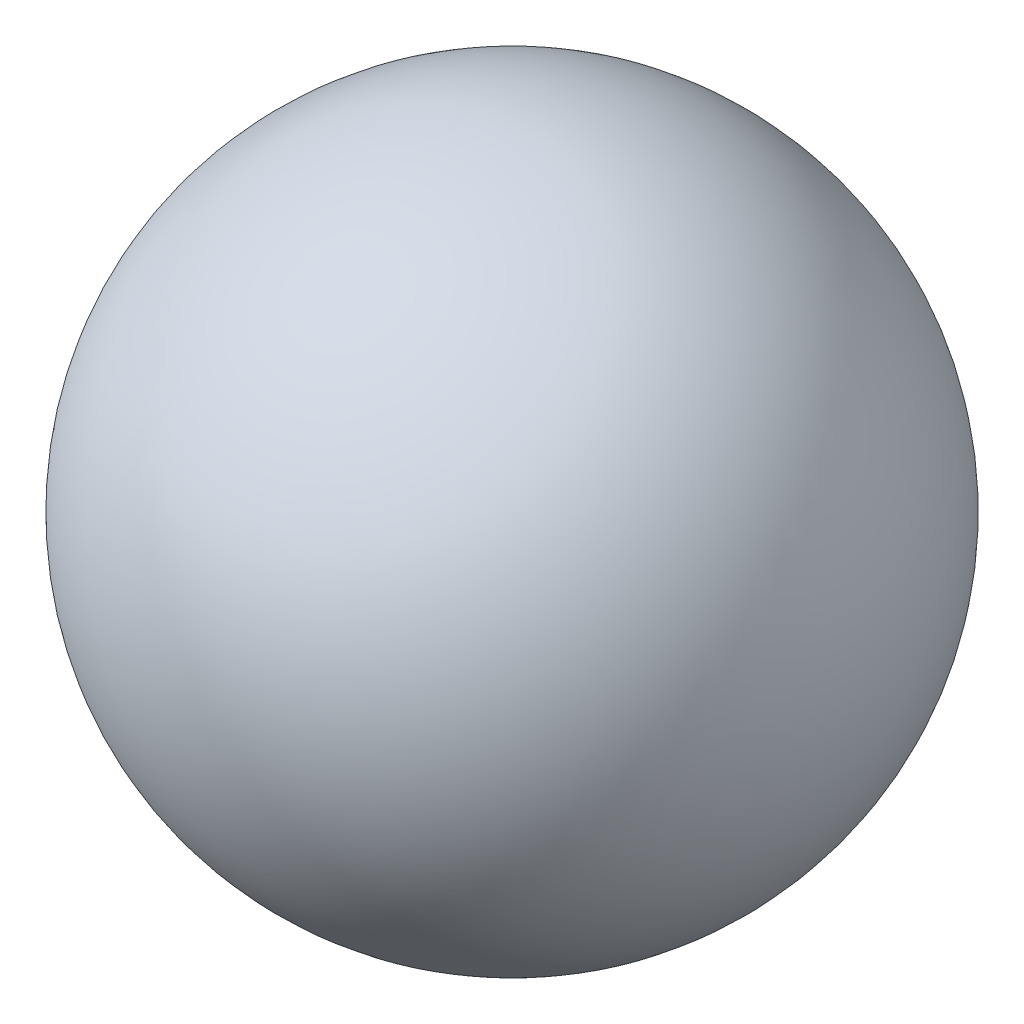
SolidWorks part; units mm, degrees
ref_plane "Alzado" through (0, 0, 0) normal (0, 0, 1) x (1, 0, 0)
ref_plane "Planta" through (0, 0, 0) normal (0, 1, 0) x (1, 0, 0)
ref_plane "Vista lateral" through (0, 0, 0) normal (1, 0, 0) x (0, 0, -1)
sketch "Croquis2" plane through (0, 0, 0) normal (0, 0, 1) x (1, 0, 0)
  line L0 (0, 5.8) -> (0, -5.8)
  circle A0 centre (0, 0) radius 5.8
  dimension "D1" = 11.6
revolve "Revolución1" add sketch "Croquis2" angle 360 about L0
